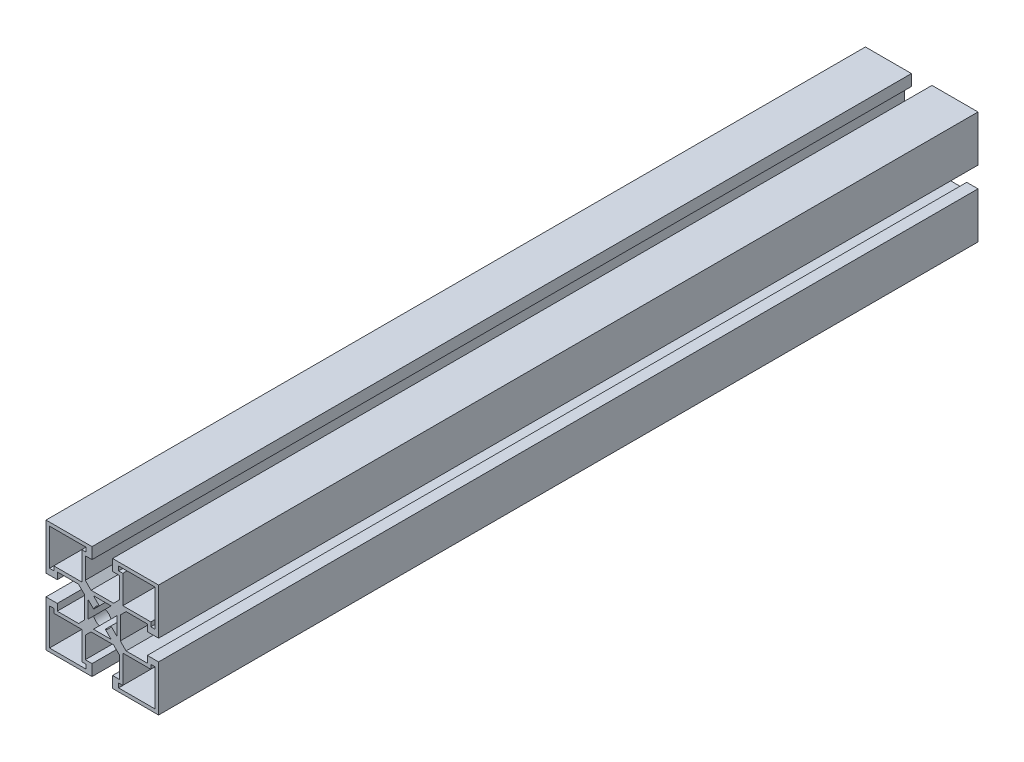
SolidWorks part; units mm, degrees
material "6061 Alloy"
ref_plane "Front Plane" through (0, 0, 0) normal (0, 0, 1) x (1, 0, 0)
ref_plane "Top Plane" through (0, 0, 0) normal (0, 1, 0) x (1, 0, 0)
ref_plane "Right Plane" through (0, 0, 0) normal (1, 0, 0) x (0, 0, -1)
sketch "Sketch1" plane through (0, 0, 0) normal (0, 0, 1) x (1, 0, 0)
  line L18 (8.2, 8.2) -> (8.2, 19.4)
  line L20 (19.4, 8.2) -> (8.2, 8.2)
  line L21 (19.4, 6.5) -> (19.4, 8.2)
  line L22 (21.1, 6.5) -> (19.4, 6.5)
  line L23 (21.1, 21.1) -> (21.1, 6.5)
  line L24 (6.5, 21.1) -> (21.1, 21.1)
  line L25 (6.5, 19.4) -> (6.5, 21.1)
  line L26 (8.2, 19.4) -> (6.5, 19.4)
  line L27 (-19.4, 6.5) -> (-21.1, 6.5)
  line L28 (-19.4, 8.2) -> (-19.4, 6.5)
  line L29 (-8.2, 8.2) -> (-19.4, 8.2)
  line L31 (-8.2, 19.4) -> (-8.2, 8.2)
  line L32 (-6.5, 19.4) -> (-8.2, 19.4)
  line L33 (-6.5, 21.1) -> (-6.5, 19.4)
  line L34 (-21.1, 21.1) -> (-6.5, 21.1)
  line L35 (-21.1, 6.5) -> (-21.1, 21.1)
  line L88 (-22.5, -22.5) -> (-4.1, -22.5)
  line L89 (-4.1, -22.5) -> (-4.1, -18)
  line L90 (-4.1, -18) -> (-6.8, -18)
  line L91 (-6.8, -18) -> (-6.8, -9.5)
  line L92 (-6.8, -9.5) -> (-4.5, -7.2)
  line L93 (-4.5, -7.2) -> (4.5, -7.2)
  line L94 (4.5, -7.2) -> (6.8, -9.5)
  line L95 (6.8, -9.5) -> (6.8, -18)
  line L96 (6.8, -18) -> (4.1, -18)
  line L97 (4.1, -18) -> (4.1, -22.5)
  line L98 (4.1, -22.5) -> (22.5, -22.5)
  line L99 (22.5, -22.5) -> (22.5, -4.1)
  line L100 (22.5, -4.1) -> (18, -4.1)
  line L101 (18, -4.1) -> (18, -6.8)
  line L102 (18, -6.8) -> (9.5, -6.8)
  line L103 (9.5, -6.8) -> (7.2, -4.5)
  line L104 (7.2, -4.5) -> (7.2, 4.5)
  line L105 (7.2, 4.5) -> (9.5, 6.8)
  line L106 (9.5, 6.8) -> (18, 6.8)
  line L107 (18, 6.8) -> (18, 4.1)
  line L108 (18, 4.1) -> (22.5, 4.1)
  line L109 (22.5, 4.1) -> (22.5, 22.5)
  line L110 (22.5, 22.5) -> (4.1, 22.5)
  line L111 (4.1, 22.5) -> (4.1, 18)
  line L112 (4.1, 18) -> (6.8, 18)
  line L113 (6.8, 18) -> (6.8, 9.5)
  line L114 (6.8, 9.5) -> (4.5, 7.2)
  line L115 (4.5, 7.2) -> (-4.5, 7.2)
  line L116 (-4.5, 7.2) -> (-6.8, 9.5)
  line L117 (-6.8, 9.5) -> (-6.8, 18)
  line L118 (-6.8, 18) -> (-4.1, 18)
  line L119 (-4.1, 18) -> (-4.1, 22.5)
  line L120 (-4.1, 22.5) -> (-22.5, 22.5)
  line L121 (-22.5, 22.5) -> (-22.5, 4.1)
  line L122 (-22.5, 4.1) -> (-18, 4.1)
  line L123 (-18, 4.1) -> (-18, 6.8)
  line L124 (-18, 6.8) -> (-9.5, 6.8)
  line L125 (-9.5, 6.8) -> (-7.2, 4.5)
  line L126 (-7.2, 4.5) -> (-7.2, -4.5)
  line L127 (-7.2, -4.5) -> (-9.5, -6.8)
  line L128 (-9.5, -6.8) -> (-18, -6.8)
  line L129 (-18, -6.8) -> (-18, -4.1)
  line L130 (-18, -4.1) -> (-22.5, -4.1)
  line L131 (-22.5, -4.1) -> (-22.5, -22.5)
  line L133 (-6.5, -21.1) -> (-21.1, -21.1)
  line L134 (-6.5, -19.4) -> (-6.5, -21.1)
  line L135 (-8.2, -19.4) -> (-6.5, -19.4)
  line L136 (-8.2, -8.2) -> (-8.2, -19.4)
  line L138 (-19.4, -8.2) -> (-8.2, -8.2)
  line L139 (-19.4, -6.5) -> (-19.4, -8.2)
  line L140 (-21.1, -6.5) -> (-19.4, -6.5)
  line L141 (-21.1, -21.1) -> (-21.1, -6.5)
  line L151 (6.5, -19.4) -> (8.2, -19.4)
  line L152 (6.5, -21.1) -> (6.5, -19.4)
  line L153 (21.1, -21.1) -> (6.5, -21.1)
  line L154 (21.1, -6.5) -> (21.1, -21.1)
  line L155 (19.4, -6.5) -> (21.1, -6.5)
  line L156 (19.4, -8.2) -> (19.4, -6.5)
  line L157 (8.2, -8.2) -> (19.4, -8.2)
  line L159 (8.2, -19.4) -> (8.2, -8.2)
  line L172 (-5.8, 3.5373) -> (-3.4511, 1.1884)
  line L173 (-5.8, -3.5373) -> (-5.8, 3.5373)
  line L174 (-3.4511, -1.1884) -> (-5.8, -3.5373)
  line L175 (-3.5373, -5.8) -> (-1.1884, -3.4511)
  line L176 (3.5373, -5.8) -> (-3.5373, -5.8)
  line L177 (1.1884, -3.4511) -> (3.5373, -5.8)
  line L178 (5.8, -3.5373) -> (3.4511, -1.1884)
  line L179 (5.8, 3.5373) -> (5.8, -3.5373)
  line L180 (3.4511, 1.1884) -> (5.8, 3.5373)
  line L181 (3.5373, 5.8) -> (1.1884, 3.4511)
  line L182 (-3.5373, 5.8) -> (3.5373, 5.8)
  line L183 (-1.1884, 3.4511) -> (-3.5373, 5.8)
  arc A4 (-1.1884, 3.4511) -> (-3.4511, 1.1884) centre (0, 0) ccw
  arc A5 (-3.4511, -1.1884) -> (-1.1884, -3.4511) centre (0, 0) ccw
  arc A6 (1.1884, -3.4511) -> (3.4511, -1.1884) centre (0, 0) ccw
  arc A7 (3.4511, 1.1884) -> (1.1884, 3.4511) centre (0, 0) ccw
extrude "Boss-Extrude1" add sketch "Sketch1" along normal blind 327.5
